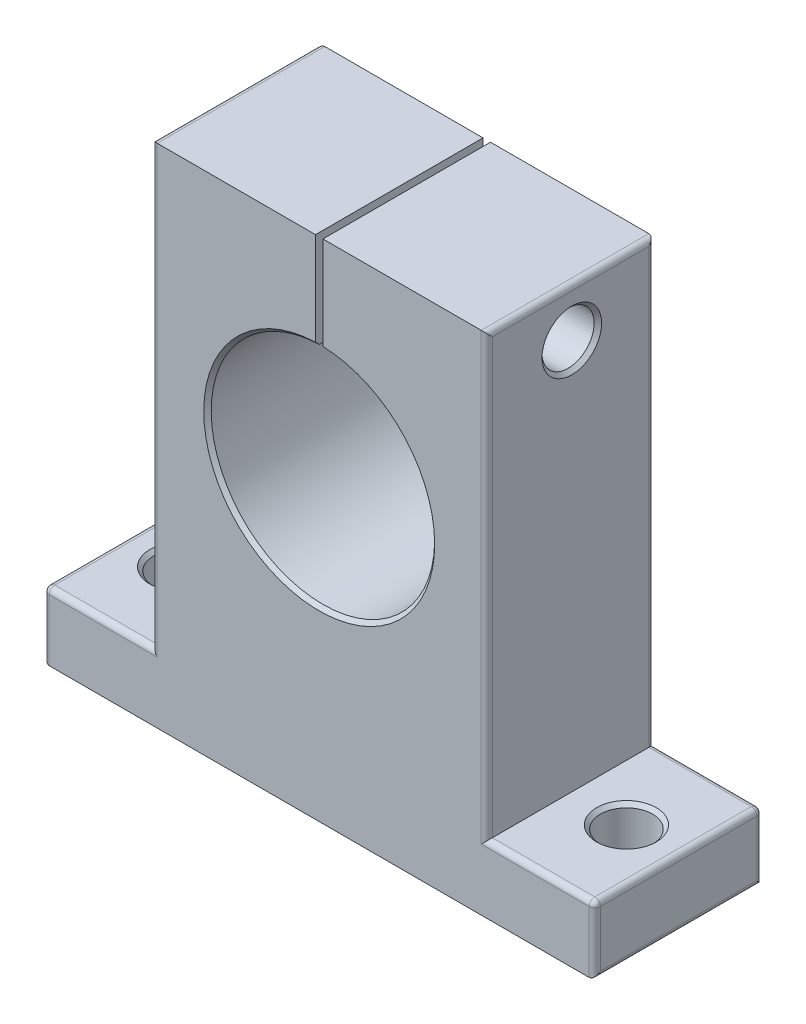
SolidWorks part; units mm, degrees
material "1060 Alloy"
ref_plane "Front Plane" through (0, 0, 0) normal (0, 0, 1) x (1, 0, 0)
ref_plane "Top Plane" through (0, 0, 0) normal (0, 1, 0) x (1, 0, 0)
ref_plane "Right Plane" through (0, 0, 0) normal (1, 0, 0) x (0, 0, -1)
sketch "Sketch1" plane through (0, 0, 0) normal (0, 0, 1) x (1, 0, 0)
  line L0 (0, 0) -> (-50000, 0) construction
  line L1 (0, 0) -> (0, 50000) construction
  line L2 (-74, -9) -> (-74, 9)
  line L3 (-74, 9) -> (-45, 9)
  line L4 (-45, 9) -> (-45, 127)
  line L5 (-45, 127) -> (-1, 127)
  line L6 (45, 127) -> (45, 9)
  line L7 (45, 9) -> (74, 9)
  line L8 (74, 9) -> (74, -9)
  line L9 (74, -9) -> (-74, -9)
  line L10 (60, -3) -> (60, 3) construction
  line L11 (-60, -3) -> (-60, 3) construction
  line L12 (-1, 127) -> (-1, 100.9833)
  line L13 (1, 127) -> (1, 100.9833)
  line L14 (1, 127) -> (45, 127)
  arc A0 (-1, 100.9833) -> (1, 100.9833) centre (0, 71) ccw
  point P8 (-74, 0)
  point P10 (24, -4)
  point P15 (0, -9)
  point P17 (0, 0)
  point P21 (60, 0)
  dimension "Shaft Diameter" = 60
  dimension "W" = 148
  dimension "P" = 90
  dimension "F" = 136
  dimension "G" = 18
  dimension "B" = 120
  dimension "D1" = 2
  dimension "h" = 80
extrude "Boss-Extrude1" add sketch "Sketch1" along normal mid plane 45
sketch "Sketch2" plane through (0, 9, 0) normal (0, 1, 0) x (1, 0, 0)
  line L0 (0, 0) -> (50000, 0) construction
  line L1 (0.3141, 0) -> (-49999.6859, 0) construction
  line L2 (0, 2.4842) -> (0, 50002.4842) construction
  circle A0 centre (60, 0) radius 7
  circle A1 centre (-60, 0) radius 7
  point P11 (17.1569, 0)
  dimension "B" = 120
  dimension "S" = 14
extrude "Cut-Extrude1" cut sketch "Sketch2" against normal through all
sketch "Sketch5" plane through (-1, 0, 0) normal (1, 0, 0) x (0, 0, -1)
  line L0 (-22.5, 113.9917) -> (22.5, 113.9917) construction
  line L1 (22.5, 100.9833) -> (22.5, 127) construction
  line L2 (0, 127) -> (0, 100.9833) construction
  line L3 (-22.5, 127) -> (22.5, 127) construction
  line L4 (-22.5, 100.9833) -> (22.5, 100.9833) construction
  line L5 (-22.5, 100.9833) -> (-22.5, 127) construction
  circle A0 centre (0.3307, 113.9917) radius 7
  dimension "Clamping bold" = 14
extrude "Cut-Extrude2" cut sketch "Sketch5" against normal through all both and the other way through all
chamfer "Chamfer2" distance 1 angle 45 6 edges at (0, 41, -22.5) (0, 41, 22.5) (-45, 113.9917, -7.3307) (-53, 9, 0) (45, 113.9917, 6.6693) (53, 9, 0)
fillet "Fillet2" radius 1.5 18 edges at (74, -9, 0) (74, 0, 22.5) (74, 9, 0) (74, 0, -22.5) (-74, 9, 0) (-74, 0, 22.5) (-74, -9, 0) (-74, 0, -22.5) (-59.5, 9, -22.5) (-59.5, 9, 22.5) (-45, 68, 22.5) (-45, 127, 0) (-45, 68, -22.5) (45, 68, -22.5) (45, 68, 22.5) (59.5, 9, 22.5) (59.5, 9, -22.5) (45, 127, 0)
equation "\"W\"= \"W@Sketch1\"'Width"
equation "\"B\"= \"B@Sketch1\"'between hold"
equation "\"F\"= \"F@Sketch1\"'Hight"
equation "\"P\"= \"P@Sketch1\""
equation "\"G\"= \"G@Sketch1\""
equation "\"Shaft diameter\"= \"Shaft Diameter@Sketch1\""
equation "\"S\" = \"S@Sketch2\"'M10"
equation "\"Clamping bold\" = \"Clamping bold@Sketch5\"'M8"
equation "\"h\"= \"h@Sketch1\""
